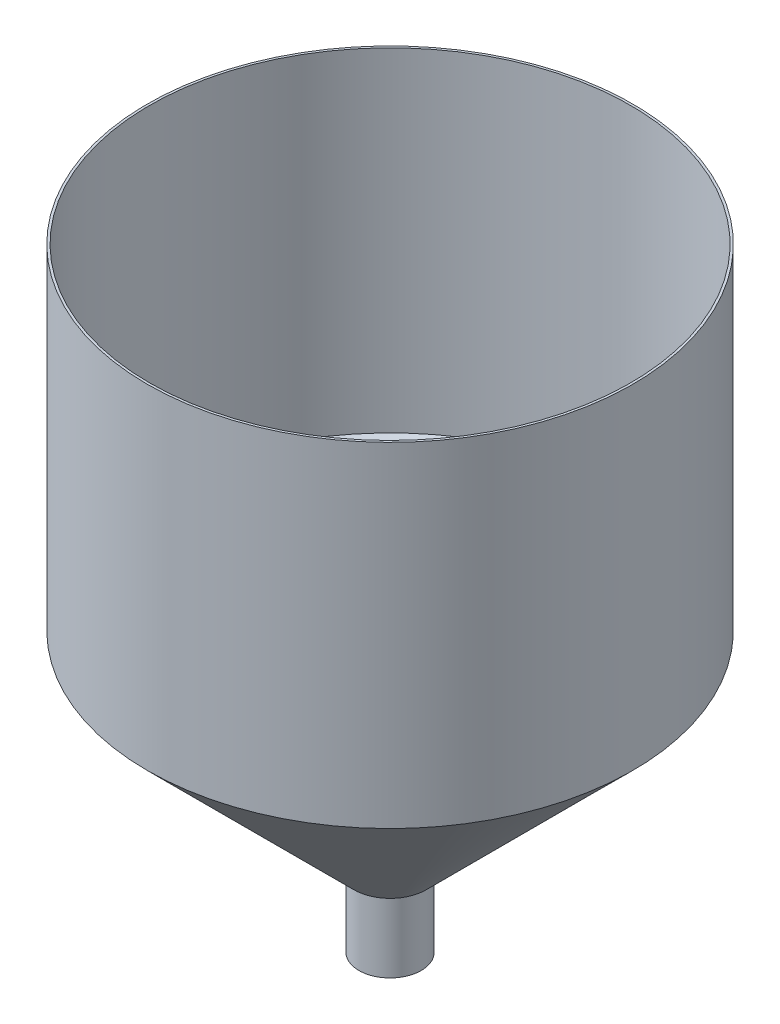
SolidWorks part; units mm, degrees
ref_plane "Alzado" through (0, 0, 0) normal (0, 0, 1) x (1, 0, 0)
ref_plane "Planta" through (0, 0, 0) normal (0, 1, 0) x (1, 0, 0)
ref_plane "Vista lateral" through (0, 0, 0) normal (1, 0, 0) x (0, 0, -1)
sketch "Croquis1" plane through (0, 0, 0) normal (0, 1, 0) x (1, 0, 0)
  circle A0 centre (0, 0) radius 334.8
  dimension "D1" = 669.6
ref_plane "Plano1" through (0, -746.1, 0) normal (0, 1, 0) x (1, 0, 0)
extrude "Saliente-Extruir1" add sketch "Croquis1" against normal blind 461.3 contours A0
sketch "Croquis2" plane through (0, -461.3, 0) normal (0, -1, 0) x (1, 0, 0)
  circle A0 centre (0, 0) radius 334.8
  circle A1 centre (0, 0) radius 334.8 construction
sketch "Croquis3" plane through (0, -746.1, 0) normal (0, 1, 0) x (1, 0, 0)
  circle A0 centre (0, 0) radius 50
  dimension "D1" = 100
loft "Recubrir1" add profiles "Croquis3", "Croquis2"
sketch "Croquis4" plane through (0, -746.1, 0) normal (0, -1, 0) x (1, 0, 0)
  circle A0 centre (0, 0) radius 43
  dimension "D1" = 86
extrude "Saliente-Extruir2" add sketch "Croquis4" along normal blind 100
ref_plane "Plano2" through (0, 0, -43) normal (0, 0, -1) x (-1, 0, 0)
shell "Vaciado1" thickness 3.175
